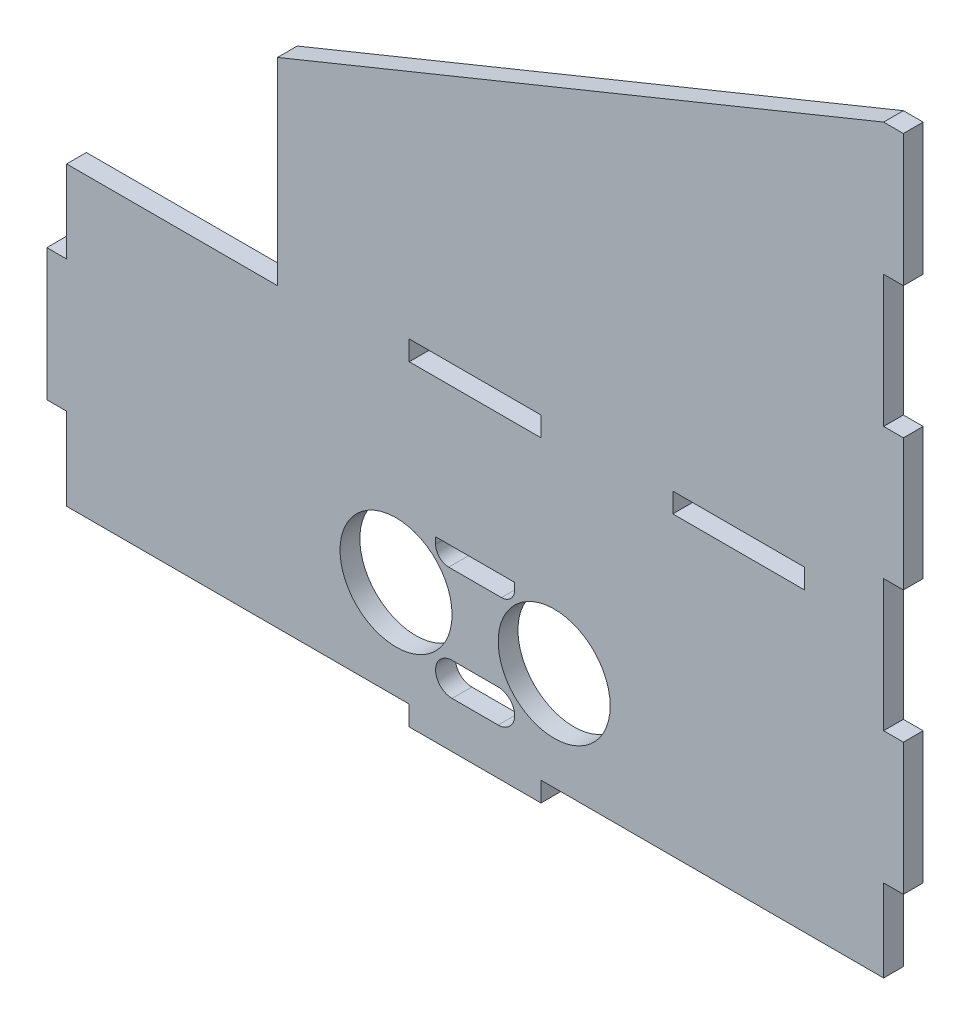
SolidWorks part; units mm, degrees
ref_plane "Front Plane" through (0, 0, 0) normal (0, 0, 1) x (1, 0, 0)
ref_plane "Top Plane" through (0, 0, 0) normal (0, 1, 0) x (1, 0, 0)
ref_plane "Right Plane" through (0, 0, 0) normal (1, 0, 0) x (0, 0, -1)
sketch "Sketch4" plane through (0, 0, 0) normal (0, 0, 1) x (1, 0, 0)
  line L0 (62, 90) -> (-30, 52.5)
  line L1 (-62, -22.5) -> (-10, -22.5)
  line L2 (-62, -22.5) -> (-62, -10)
  line L3 (-62, 22.5) -> (-30, 22.5)
  line L4 (62, -22.5) -> (62, -10)
  line L5 (-62, -22.5) -> (62, 22.5) construction
  line L6 (-62, 22.5) -> (62, -22.5) construction
  line L11 (-62, 10) -> (-65, 10)
  line L13 (-62, -10) -> (-65, -10)
  line L14 (-65, 10) -> (-65, -10)
  line L15 (-10, -25.5) -> (10, -25.5)
  line L16 (10, -22.5) -> (10, -25.5)
  line L18 (-10, -22.5) -> (-10, -25.5)
  line L19 (0, -55) -> (0, 55) construction
  line L20 (62, -10) -> (65, -10)
  line L21 (65, 10) -> (65, -10)
  line L22 (62, 10) -> (65, 10)
  line L25 (-62, 10) -> (-62, 22.5)
  line L26 (10, -22.5) -> (62, -22.5)
  line L27 (62, 10) -> (62, 22.5)
  line L28 (-3.5, -16) -> (3.5, -16) construction
  line L37 (-3.5, -13.5) -> (3.5, -13.5)
  line L38 (-3.5, -18.5) -> (3.5, -18.5)
  line L39 (62, 50) -> (62, 70)
  line L40 (4, -1.5) -> (-4, -1.5)
  line L41 (6, 0.5) -> (6, 1.5)
  line L42 (6, 1.5) -> (-6, 1.5)
  line L43 (-6, 0.5) -> (-6, 1.5)
  line L44 (6, -1.5) -> (-6, 1.5) construction
  line L45 (6, 1.5) -> (-6, -1.5) construction
  line L51 (-30, 22.5) -> (-30, 52.5)
  line L53 (62, 22.5) -> (62, 30)
  line L54 (62, 30) -> (65, 30)
  line L56 (62, 50) -> (65, 50)
  line L57 (65, 30) -> (65, 50)
  line L58 (62, 70) -> (65, 70)
  line L60 (62, 90) -> (65, 90)
  line L61 (65, 70) -> (65, 90)
  line L63 (-10, 22.5) -> (10, 22.5)
  line L64 (-10, 22.5) -> (-10, 25.5)
  line L65 (-10, 25.5) -> (10, 25.5)
  line L66 (10, 22.5) -> (10, 25.5)
  line L67 (-10, 22.5) -> (10, 25.5) construction
  line L68 (-10, 25.5) -> (10, 22.5) construction
  line L69 (30, 22.5) -> (50, 22.5)
  line L70 (30, 22.5) -> (30, 25.5)
  line L71 (30, 25.5) -> (50, 25.5)
  line L72 (50, 22.5) -> (50, 25.5)
  circle A0 centre (-12, -7.5) radius 8.5
  circle A1 centre (12, -7.5) radius 8.5
  arc A6 (-3.5, -13.5) -> (-3.5, -18.5) centre (-3.5, -16) ccw
  arc A7 (3.5, -18.5) -> (3.5, -13.5) centre (3.5, -16) ccw
  arc A8 (4, -1.5) -> (6, 0.5) centre (4, 0.5) ccw
  arc A9 (-4, -1.5) -> (-6, 0.5) centre (-4, 0.5) cw
  point P0 (0, 0)
  point P31 (0, -16)
  point P38 (0, 0)
  point P50 (0, 24)
  dimension "D9" = 17
  dimension "D10" = 17
  dimension "D11" = 24
  dimension "D17" = 3
  dimension "D15" = 2.5
  dimension "D20" = 2
  dimension "D1" = 45
  dimension "D2" = 124
  dimension "D3" = 67.5
  dimension "D4" = 32
  dimension "D5" = 3
  dimension "D6" = 3
  dimension "D7" = 20
  dimension "D8" = 12.5
  dimension "D12" = 15
  dimension "D13" = 12
  dimension "D14" = 7
  dimension "D16" = 6
  dimension "D18" = 12
  dimension "D19" = 6
  dimension "D21" = 20
  dimension "D22" = 52
  dimension "D23" = 3
  dimension "D24" = 20
  dimension "D25" = 20
  dimension "D26" = 20
  dimension "D27" = 20
  dimension "D28" = 3
  dimension "D29" = 30
  dimension "D30" = 20
  dimension "D31" = 3
  dimension "D32" = 20
  dimension "D33" = 3
  dimension "D34" = 20
extrude "Boss-Extrude2" add sketch "Sketch4" along normal blind 3
